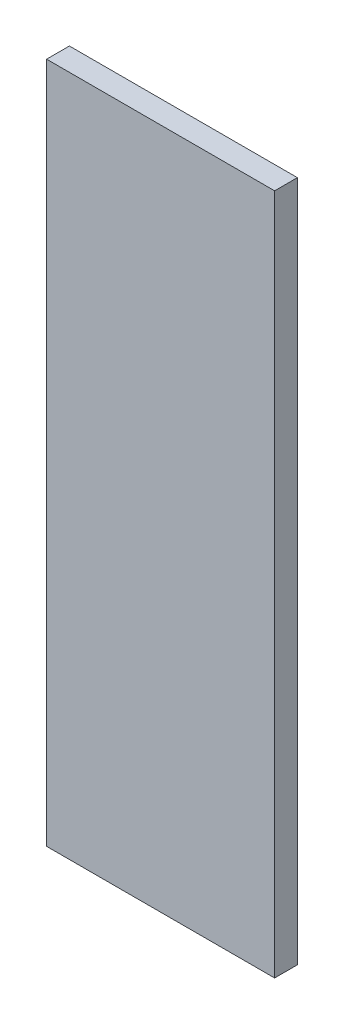
SolidWorks part; units mm, degrees
ref_plane "Front Plane" through (0, 0, 0) normal (0, 0, 1) x (1, 0, 0)
ref_plane "Top Plane" through (0, 0, 0) normal (0, 1, 0) x (1, 0, 0)
ref_plane "Right Plane" through (0, 0, 0) normal (1, 0, 0) x (0, 0, -1)
sketch "Sketch1" plane through (0, 0, 0) normal (0, 0, 1) x (1, 0, 0)
  line L1 (-20, 59.8) -> (20, 59.8)
  line L2 (-20, 59.8) -> (-20, -59.8)
  line L3 (-20, -59.8) -> (20, -59.8)
  line L4 (20, 59.8) -> (20, -59.8)
  line L5 (-20, 59.8) -> (20, -59.8) construction
  line L6 (-20, -59.8) -> (20, 59.8) construction
  point P0 (0, 0)
  dimension "D1" = 40
  dimension "D2" = 119.6
extrude "Boss-Extrude1" add sketch "Sketch1" along normal blind 4
